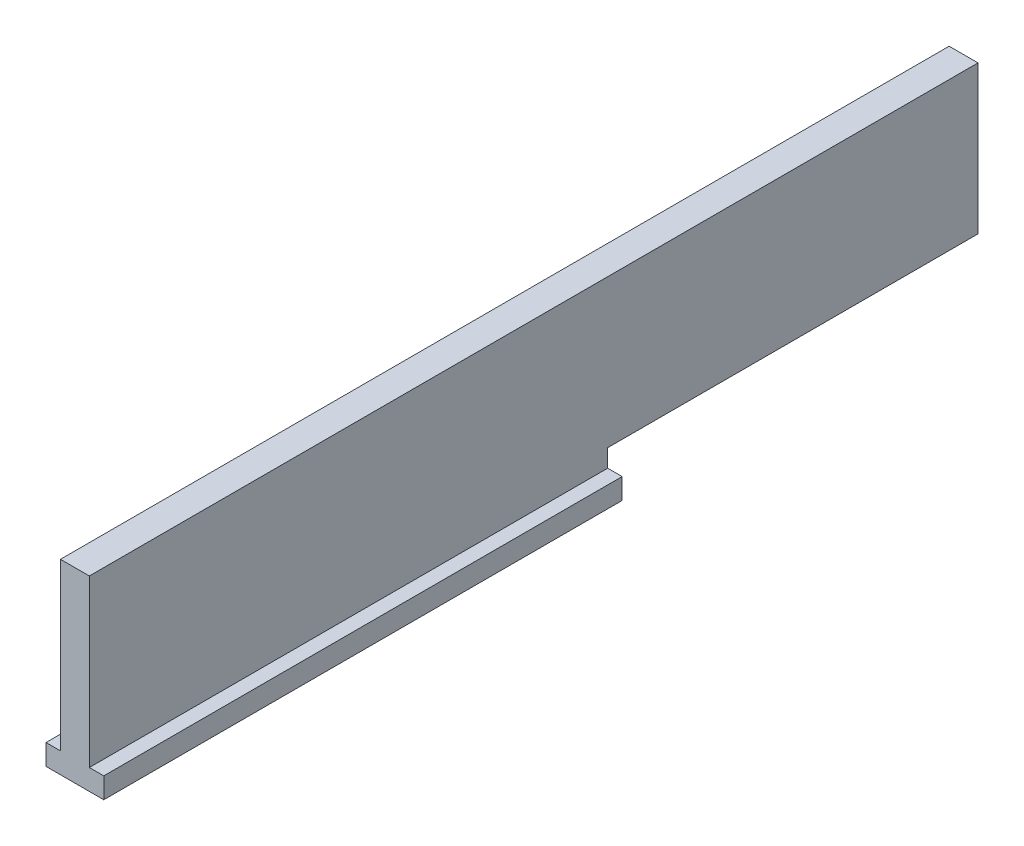
SolidWorks part; units mm, degrees
ref_plane "Alzado" through (0, 0, 0) normal (0, 0, 1) x (1, 0, 0)
ref_plane "Planta" through (0, 0, 0) normal (0, 1, 0) x (1, 0, 0)
ref_plane "Vista lateral" through (0, 0, 0) normal (1, 0, 0) x (0, 0, -1)
sketch "Croquis1" plane through (0, 0, 0) normal (0, 0, 1) x (1, 0, 0)
  line L0 (0, 0) -> (0, 5.0002) construction
  line L1 (-1.95, 0) -> (1.95, 0) construction
  line L2 (-1.95, -0.7) -> (-1.95, 0.7)
  line L3 (1.95, 0.7) -> (1.95, -0.7)
  line L4 (-1.95, -0.7) -> (1.95, -0.7)
  line L5 (-0.975, 0.7) -> (0.975, 0.7) construction
  line L6 (-1.95, 0.7) -> (-0.975, 0.7)
  line L7 (1.95, 0.7) -> (0.975, 0.7)
  line L8 (-0.975, 0.7) -> (-0.975, 1.9)
  line L9 (-0.975, 1.9) -> (0.975, 1.9)
  line L10 (0.975, 0.7) -> (0.975, 1.9)
  point P6 (0, 0)
  point P9 (-1.95, 0)
  point P13 (1.95, 0)
  point P15 (0, 0.7)
  dimension "D1" = 3.9
  dimension "D2" = 1.4
  dimension "D3" = 1.4
  dimension "D4" = 1.95
  dimension "D5" = 1.2
extrude "Saliente-Extruir1" add sketch "Croquis1" against normal blind 35
sketch "Croquis9" plane through (0, 0, 0) normal (1, 0, 0) x (0, 0, -1)
  line L0 (0, 1.9) -> (60, 1.9) construction
  line L1 (0, 11.9) -> (60, 11.9)
  line L6 (0, 1.9) -> (0, 11.9)
  line L9 (60, 11.9) -> (60, 1.9)
  line L10 (60, 1.9) -> (0, 1.9)
  dimension "D1" = 60
  dimension "D4" = 10
extrude "Saliente-Extruir2" add sketch "Croquis9" along normal mid plane 1.95
